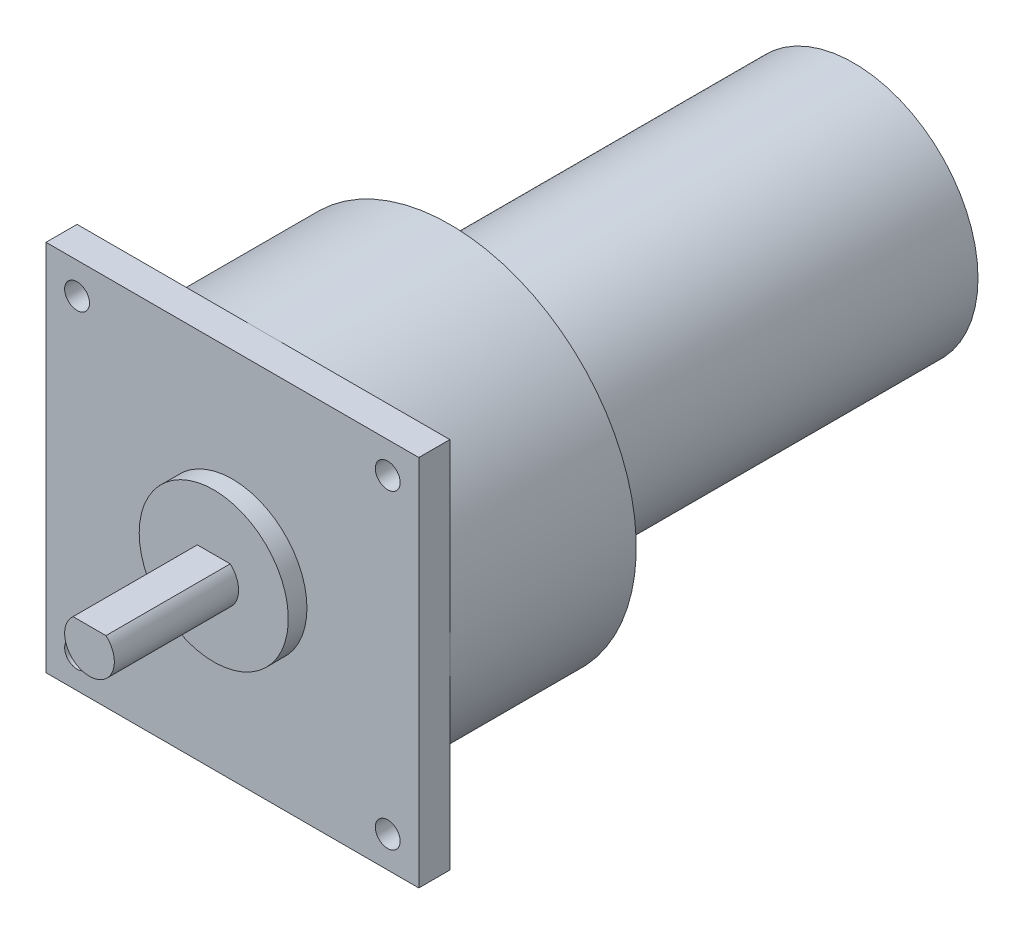
SolidWorks part; units mm, degrees
ref_plane "Front Plane" through (0, 0, 0) normal (0, 0, 1) x (1, 0, 0)
ref_plane "Top Plane" through (0, 0, 0) normal (0, 1, 0) x (1, 0, 0)
ref_plane "Right Plane" through (0, 0, 0) normal (1, 0, 0) x (0, 0, -1)
sketch "Sketch1" plane through (0, 0, 0) normal (0, 0, 1) x (1, 0, 0)
  line L1 (-30, 30) -> (30, 30)
  line L2 (-30, 30) -> (-30, -30)
  line L3 (-30, -30) -> (30, -30)
  line L4 (30, 30) -> (30, -30)
  line L5 (-30, 30) -> (30, -30) construction
  line L6 (-30, -30) -> (30, 30) construction
  point P0 (0, 0)
  dimension "D1" = 60
  dimension "D2" = 60
extrude "Boss-Extrude1" add sketch "Sketch1" along normal blind 5
sketch "Sketch2" plane through (0, 0, 0) normal (0, 0, -1) x (-1, 0, 0)
  line L0 (0, 30) -> (0, -30) construction
  line L1 (-30, 30) -> (30, 30) construction
  line L2 (30, -30) -> (-30, -30) construction
  line L3 (-30, 0) -> (30, 0) construction
  line L4 (-30, -30) -> (-30, 30) construction
  line L5 (30, 30) -> (30, -30) construction
  circle A0 centre (-25, 25) radius 2
  circle A1 centre (25, 25) radius 2
  circle A2 centre (25, -25) radius 2
  circle A3 centre (-25, -25) radius 2
  dimension "D3" = 4
  dimension "D1" = 25
  dimension "D2" = 25
  dimension "D4" = 2
  dimension "D5" = 2
extrude "hole" cut sketch "Sketch2" against normal up to surface (5 mm away) up to face at (0, 0, 5)
sketch "Sketch3" plane through (0, 0, 0) normal (0, 0, -1) x (-1, 0, 0)
  circle A0 centre (0, 0) radius 12
extrude "Boss-Extrude2" add sketch "Sketch3" against normal blind 8
sketch "Sketch4" plane through (0, 0, 8) normal (0, 0, 1) x (1, 0, 0)
  line L0 (0, -4) -> (0, 4) construction
  line L2 (-2.6458, 3) -> (2.6458, 3)
  arc A0 (-2.6458, 3) -> (2.6458, 3) centre (0, 0) ccw
  dimension "D1" = 7
  dimension "D2" = 4
extrude "shaft" add sketch "Sketch4" along normal blind 20
sketch "Sketch5" plane through (0, 0, 0) normal (0, 0, -1) x (-1, 0, 0)
  circle A0 centre (0, 0) radius 30
extrude "gear" add sketch "Sketch5" along normal blind 30
sketch "Sketch6" plane through (0, 0, -30) normal (0, 0, -1) x (-1, 0, 0)
  circle A0 centre (0, 0) radius 20
extrude "motor" add sketch "Sketch6" along normal blind 65
